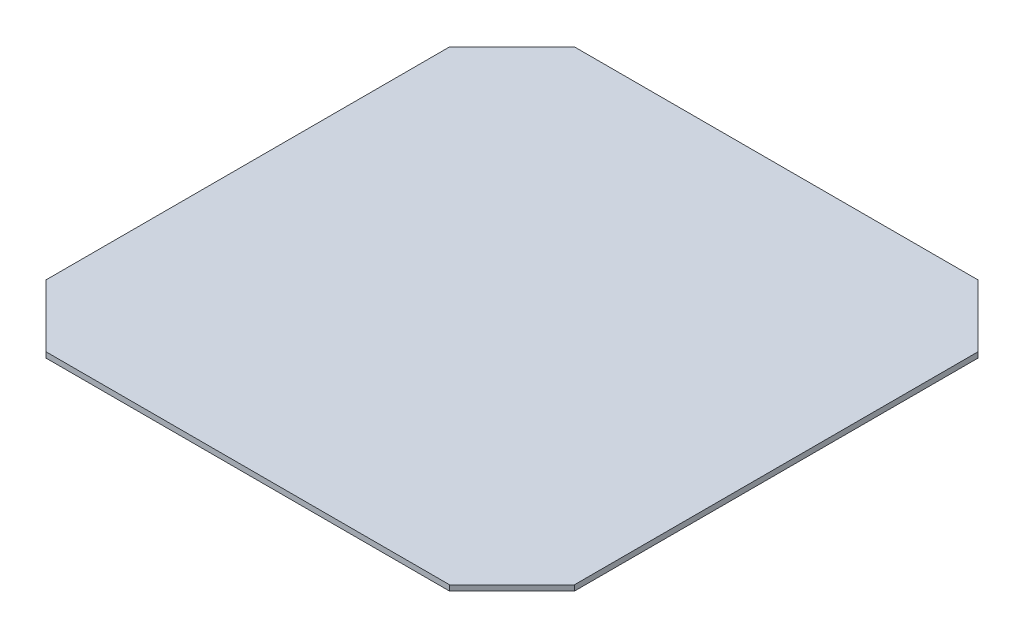
SolidWorks part; units mm, degrees
ref_plane "Front Plane" through (0, 0, 0) normal (0, 0, 1) x (1, 0, 0)
ref_plane "Top Plane" through (0, 0, 0) normal (0, 1, 0) x (1, 0, 0)
ref_plane "Right Plane" through (0, 0, 0) normal (1, 0, 0) x (0, 0, -1)
sketch "Sketch1" plane through (0, 0, 0) normal (0, 1, 0) x (1, 0, 0)
  line L0 (-61.766, 15.7353) -> (-25.845, 51.6564)
  line L1 (-61.766, 51.6564) -> (243.034, 51.6564)
  line L2 (-61.766, 51.6564) -> (-61.766, -253.1436)
  line L3 (-61.766, -253.1436) -> (243.034, -253.1436)
  line L4 (243.034, 51.6564) -> (243.034, -253.1436)
  line L5 (90.634, 95.069) -> (90.634, -294.9418) construction
  line L6 (-86.5248, -100.7436) -> (277.558, -100.7436) construction
  line L7 (243.034, 15.7353) -> (207.1129, 51.6564)
  line L8 (243.034, -217.2226) -> (207.1129, -253.1436)
  line L9 (-61.766, -217.2226) -> (-25.845, -253.1436)
  point P8 (90.634, 51.6564)
  point P11 (-61.766, -100.7436)
  dimension "D1" = 304.8
  dimension "D2" = 304.8
  dimension "D3" = 45
  dimension "D4" = 50.8
extrude "Boss-Extrude1" add sketch "Sketch1" along normal blind 3.175
